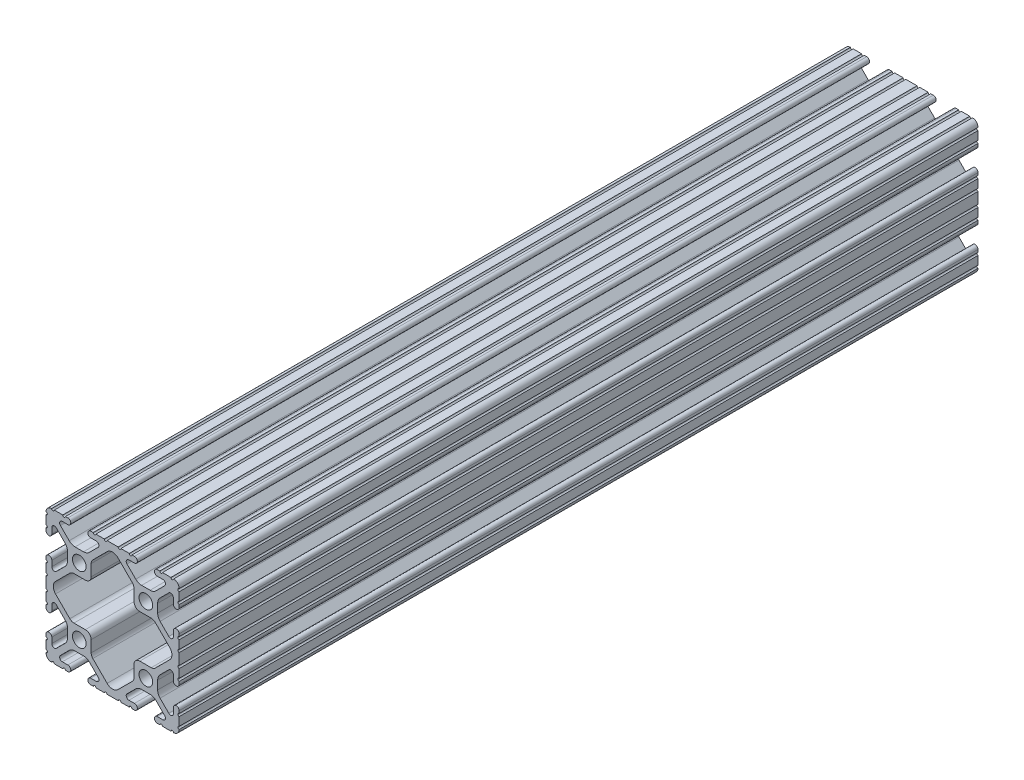
SolidWorks part; units mm, degrees
material "6061 Alloy"
ref_plane "Front Plane" through (0, 0, 0) normal (0, 0, 1) x (1, 0, 0)
ref_plane "Top Plane" through (0, 0, 0) normal (0, 1, 0) x (1, 0, 0)
ref_plane "Right Plane" through (0, 0, 0) normal (1, 0, 0) x (0, 0, -1)
sketch "Sketch1" plane through (0, 0, 0) normal (0, 0, 1) x (1, 0, 0)
  line L0 (-25.4, 0) -> (25.4, 0) construction
  line L1 (0, 25.4) -> (0, -25.4) construction
  line L2 (-12.7, 12.7) -> (-25.4, 25.4) construction
  line L3 (-25.4, 23.8374) -> (-15.1482, 13.5857) construction
  line L4 (-23.8374, 25.4) -> (-13.5857, 15.1482) construction
  line L5 (9.4488, 25.4) -> (15.9512, 25.4) construction
  line L6 (12.7, 25.4) -> (12.7, 17.1958) construction
  line L7 (5.2832, 23.1902) -> (20.1168, 23.1902) construction
  circle A0 centre (-12.7, 12.7) radius 2.6035 construction
  circle A1 centre (12.7, 12.7) radius 2.6035 construction
  circle A2 centre (12.7, -12.7) radius 2.6035 construction
  circle A3 centre (-12.7, -12.7) radius 2.6035 construction
  circle A4 centre (0, 0) radius 12.4841 construction
  point P4 (0, 0)
  point P8 (0, 0)
  point P26 (12.7, 25.4)
  point P28 (12.7, 23.1902)
  dimension "Center Hole Diameter" = 5.207
  dimension "D5" = 24.9682
  dimension "Rail Width" = 50.8
  dimension "Rail Height" = 50.8
  dimension "D1" = 25.4
  dimension "D2" = 25.4
  dimension "D3" = 2.2098
  dimension "T Slot Width" = 6.5024
  dimension "T Slot Depth" = 8.2042
  dimension "Thickness" = 2.2098
  dimension "D4" = 14.8336
sketch "Sketch2" plane through (0, 0, 0) normal (1, 0, 0) x (0, 0, -1)
  line L0 (152.4, 0) -> (-152.4, 0)
  point P0 (-101.6, 0)
  point P4 (0, 0)
  point P5 (101.6, 0)
  point P6 (152.4, 25.4)
  point P7 (-152.4, 25.4)
  dimension "Length" = 304.8
  dimension "D1" = 50.8
  dimension "D2" = 50.8
sketch "Sketch3" plane through (0, 0, 0) normal (0, 0, 1) x (1, 0, 0)
  line L0 (-25.4, 0) -> (-25.4, 8.3439)
  line L2 (-23.1902, 8.3439) -> (-23.1902, 6.2252)
  line L3 (-21.4558, 5.5068) -> (-18.1257, 8.8368)
  line L4 (-17.1958, 11.0819) -> (-17.1958, 14.3181)
  line L5 (-18.1257, 16.5632) -> (-21.4558, 19.8932)
  line L6 (-23.1902, 19.1748) -> (-23.1902, 17.0561)
  line L8 (-25.4, 17.0561) -> (-25.4, 23.2918)
  line L9 (-23.2918, 25.4) -> (-17.0561, 25.4)
  line L11 (-17.0561, 23.1902) -> (-19.1748, 23.1902)
  line L12 (-19.8932, 21.4558) -> (-16.5632, 18.1257)
  line L13 (-14.3181, 17.1958) -> (-11.0819, 17.1958)
  line L14 (-8.8368, 18.1257) -> (-5.5068, 21.4558)
  line L15 (-6.2252, 23.1902) -> (-8.3439, 23.1902)
  line L17 (-8.3439, 25.4) -> (0, 25.4)
  line L18 (0, 25.4) -> (0, 22.6275)
  line L19 (-2.0655, 21.772) -> (-7.5331, 16.3043)
  line L20 (-8.1804, 14.7417) -> (-8.1804, 10.3902)
  line L21 (-10.3902, 8.1804) -> (-14.7417, 8.1804)
  line L22 (-16.3043, 7.5331) -> (-21.772, 2.0655)
  line L23 (-22.6275, 0) -> (-25.4, 0)
  line L24 (0, 25.4) -> (0, -25.4) construction
  line L25 (-12.7, 12.7) -> (-25.4, 25.4) construction
  line L26 (-25.4, 0) -> (25.4, 0) construction
  line L27 (5.2832, 23.1902) -> (20.1168, 23.1902) construction
  line L28 (-9.4488, 24.2951) -> (-15.9512, 24.2951) construction
  line L30 (9.4488, 25.4) -> (15.9512, 25.4) construction
  line L31 (-23.8374, 25.4) -> (-13.5857, 15.1482) construction
  line L32 (-25.4, 23.8374) -> (-15.1482, 13.5857) construction
  arc A0 (-7.5331, 16.3043) -> (-8.1804, 14.7417) centre (-5.9706, 14.7417) ccw
  circle A1 centre (-12.7, 12.7) radius 2.6035 construction
  circle A2 centre (-12.7, 12.7) radius 2.6035
  arc A3 (-8.1804, 10.3902) -> (-10.3902, 8.1804) centre (-10.3902, 10.3902) cw
  arc A4 (-14.7417, 8.1804) -> (-16.3043, 7.5331) centre (-14.7417, 5.9706) ccw
  arc A5 (-21.772, 2.0655) -> (-22.6275, 0) centre (-19.7065, 0) ccw
  arc A6 (0, 22.6275) -> (-2.0655, 21.772) centre (0, 19.7065) ccw
  circle A7 centre (0, 0) radius 12.4841 construction
  arc A8 (-17.0561, 23.1902) -> (-17.0561, 25.4) centre (-17.0561, 24.2951) ccw
  arc A9 (-8.3439, 25.4) -> (-8.3439, 23.1902) centre (-8.3439, 24.2951) ccw
  arc A10 (-25.4, 17.0561) -> (-23.1902, 17.0561) centre (-24.2951, 17.0561) ccw
  arc A11 (-23.1902, 8.3439) -> (-25.4, 8.3439) centre (-24.2951, 8.3439) ccw
  arc A12 (-25.4, 23.2918) -> (-23.2918, 25.4) centre (-23.2918, 23.2918) cw
  arc A13 (-5.5068, 21.4558) -> (-6.2252, 23.1902) centre (-6.2252, 22.1742) ccw
  arc A14 (-19.1748, 23.1902) -> (-19.8932, 21.4558) centre (-19.1748, 22.1742) ccw
  arc A15 (-21.4558, 19.8932) -> (-23.1902, 19.1748) centre (-22.1742, 19.1748) ccw
  arc A16 (-21.4558, 5.5068) -> (-23.1902, 6.2252) centre (-22.1742, 6.2252) cw
  arc A17 (-8.8368, 18.1257) -> (-11.0819, 17.1958) centre (-11.0819, 20.3708) cw
  arc A18 (-14.3181, 17.1958) -> (-16.5632, 18.1257) centre (-14.3181, 20.3708) cw
  arc A19 (-18.1257, 16.5632) -> (-17.1958, 14.3181) centre (-20.3708, 14.3181) cw
  arc A20 (-17.1958, 11.0819) -> (-18.1257, 8.8368) centre (-20.3708, 11.0819) cw
  point P37 (-12.7, 24.2951)
  point P87 (-17.1958, 12.7)
  dimension "D1" = 2.2098
  dimension "D2" = 2.921
  dimension "D3" = 2.1082
  dimension "D4" = 1.016
  dimension "D5" = 3.175
  dimension "D6" = 2.2098
extrude "Boss-Extrude1" add sketch "Sketch3" along normal up to vertex (152.4 mm away) and the other way up to vertex (152.4 mm away) up to point (0, 0, 152.4) other way up to point (0, 0, -152.4)
sketch "Sketch4" plane through (0, 0, 152.4) normal (0, 0, 1) x (1, 0, 0)
  line L0 (-12.7, 12.7) -> (-25.4, 25.4) construction
  line L1 (-12.7, 12.7) -> (-25.4, 25.4) construction
  line L2 (-12.7, 12.7) -> (-25.4, 12.7) construction
  circle A0 centre (-25.4, 2.6416) radius 0.508
  circle A1 centre (-25.4, 6.8834) radius 0.508
  circle A2 centre (-25.4, 18.5166) radius 0.508
  circle A3 centre (-25.4, 22.7584) radius 0.508
  circle A4 centre (-22.7584, 25.4) radius 0.508
  circle A5 centre (-18.5166, 25.4) radius 0.508
  circle A6 centre (-6.8834, 25.4) radius 0.508
  circle A7 centre (-2.6416, 25.4) radius 0.508
  dimension "D1" = 1.016
  dimension "D2" = 2.6416
  dimension "D3" = 4.2418
extrude "Cut-Extrude1" cut sketch "Sketch4" against normal through all
pattern_circular "CirPattern1" count 4 over 360 about axis through (0, 0, 0) along (0, 0, 1) of bodies 105
combine bodies "Combine1" bodies to combine 105 108 107 106
sketch "Sketch5" plane through (0, 0, 0) normal (0, 0, 1) x (1, 0, 0)
  circle A2 centre (-12.7, -12.7) radius 2.6035 construction
  circle A3 centre (-12.7, -12.7) radius 2.6035
  arc A4 (8.3439, -25.4) -> (8.3439, -23.1902) centre (8.3439, -24.2951) ccw construction
  arc A5 (8.3439, -25.4) -> (8.3439, -23.1902) centre (8.3439, -24.2951) ccw
  arc A6 (17.0561, -23.1902) -> (17.0561, -25.4) centre (17.0561, -24.2951) ccw construction
  arc A7 (17.0561, -23.1902) -> (17.0561, -25.4) centre (17.0561, -24.2951) ccw
  arc A8 (14.3181, 17.1958) -> (16.5632, 18.1257) centre (14.3181, 20.3708) ccw construction
  arc A9 (14.3181, 17.1958) -> (16.5632, 18.1257) centre (14.3181, 20.3708) ccw
  point P0 (-25.4, 25.4)
  point P1 (-25.4, -25.4)
  point P3 (25.4, 25.4)
  point P4 (25.4, -25.4)
  point P5 (-15.3035, -12.7)
  point P11 (-10.0965, -12.7)
  point P13 (15.9512, -24.2951)
  point P19 (9.4488, -24.2951)
  point P24 (14.3181, 17.1958)
sketch "Sketch6" plane through (0, 0, 0) normal (1, 0, 0) x (0, 0, -1)
  point P0 (-152.4, 25.4)
  point P1 (-101.6, 0)
  point P3 (101.6, 0)
  point P5 (152.4, 25.4)
equation "\"D2@Sketch1\"=\"D1@Sketch1\""
equation "\"D1@Sketch2\"=\"Rail Width@Sketch1\""
equation "\"D2@Sketch2\"=\"D1@Sketch2\""
equation "\"D6@Sketch3\"=\"Thickness@Sketch1\""
